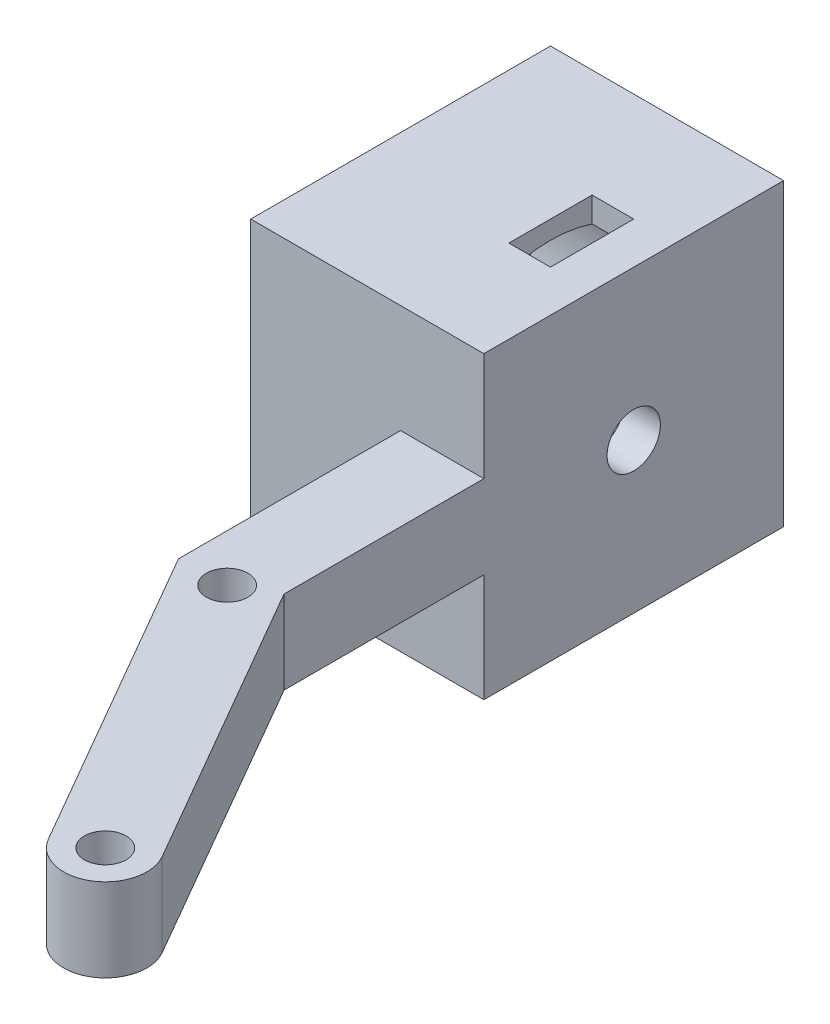
SolidWorks part; units mm, degrees
material "TPU 74D"
ref_plane "Front Plane" through (0, 0, 0) normal (0, 0, 1) x (1, 0, 0)
ref_plane "Top Plane" through (0, 0, 0) normal (0, 1, 0) x (1, 0, 0)
ref_plane "Right Plane" through (0, 0, 0) normal (1, 0, 0) x (0, 0, -1)
sketch "Sketch1" plane through (0, 0, 0) normal (0, 1, 0) x (1, 0, 0)
  line L0 (-6.35, -14.4015) -> (-6.35, 2.54)
  line L1 (0, -12.7) -> (0, 25.4)
  line L2 (0, 25.4) -> (-17.78, 25.4)
  line L3 (-17.78, 25.4) -> (-17.78, 2.54)
  line L4 (-17.78, 2.54) -> (-6.35, 2.54)
  line L5 (0, -12.7) -> (12.7, -34.697)
  line L6 (-6.35, -14.4015) -> (7.2007, -37.872)
  line L7 (0, -12.7) -> (-5.4993, -15.875) construction
  arc A0 (7.2007, -37.872) -> (12.7, -34.697) centre (9.9504, -36.2845) ccw
  circle A1 centre (9.9504, -36.2845) radius 1.5875
  circle A2 centre (-2.7496, -14.2875) radius 1.5875
  dimension "D1" = 3.175
  dimension "D2" = 3.175
  dimension "D6" = 3.175
  dimension "D3" = 150
  dimension "D4" = 6.35
  dimension "D8" = 25.4
  dimension "D10" = 17.78
  dimension "D11" = 38.1
  dimension "D12" = 22.86
  dimension "D13" = 12.7
extrude "Boss-Extrude1" add sketch "Sketch1" along normal blind 22.86
sketch "Sketch2" plane through (0, 22.86, 0) normal (0, 1, 0) x (1, 0, 0)
  line L1 (-6.35, -14.4015) -> (8.7882, -40.6217)
  line L2 (0, -12.7) -> (14.2875, -37.4467)
  line L3 (14.2875, -37.4467) -> (8.7882, -40.6217)
  line L4 (-6.35, -14.4015) -> (7.2007, -37.872) construction
  line L5 (12.7, -34.697) -> (0, -12.7) construction
  line L6 (-6.35, 2.54) -> (0, 2.54)
  line L7 (0, -12.7) -> (0, 25.4) construction
  line L8 (0, 2.54) -> (0, -12.7)
  line L9 (-6.35, -14.4015) -> (-6.35, 2.54)
  arc A0 (7.2007, -37.872) -> (12.7, -34.697) centre (9.9504, -36.2845) ccw construction
extrude "Top Cut" cut sketch "Sketch2" against normal blind 8.255
sketch "Sketch4" plane through (0, 0, 0) normal (0, -1, 0) x (1, 0, 0)
  line L0 (-6.35, -2.54) -> (-6.35, 14.4015)
  line L1 (-6.35, 14.4015) -> (7.2007, 37.872) construction
  line L2 (-6.35, -2.54) -> (-6.35, 14.4015) construction
  line L3 (-6.35, 14.4015) -> (8.7882, 40.6217)
  line L4 (8.7882, 40.6217) -> (14.2875, 37.4467)
  line L5 (-6.35, -2.54) -> (0, -2.54)
  line L7 (0, -2.54) -> (0, 12.7)
  line L8 (0, 12.7) -> (14.2875, 37.4467)
  line L9 (12.7, 34.697) -> (0, 12.7) construction
  arc A0 (12.7, 34.697) -> (7.2007, 37.872) centre (9.9504, 36.2845) ccw construction
extrude "Bottom Cut" cut sketch "Sketch4" against normal blind 8.255
sketch "Sketch3" plane through (0, 22.86, 0) normal (0, 1, 0) x (1, 0, 0)
  line L0 (-17.78, 25.4) -> (-19.05, 24.13)
  line L1 (-19.05, 24.13) -> (-17.78, 22.86)
  line L2 (-17.78, 25.4) -> (-17.78, 2.54) construction
  line L12 (-17.78, 25.4) -> (0, 25.4)
  line L13 (0, 25.4) -> (0, 0)
  line L14 (0, 2.54) -> (0, 25.4) construction
  line L16 (-19.05, 21.59) -> (-17.78, 20.32)
  line L17 (-17.78, 22.86) -> (-19.05, 21.59)
  line L18 (-19.05, 19.05) -> (-17.78, 17.78)
  line L19 (-17.78, 20.32) -> (-19.05, 19.05)
  line L20 (-19.05, 16.51) -> (-17.78, 15.24)
  line L21 (-17.78, 17.78) -> (-19.05, 16.51)
  line L22 (-19.05, 13.97) -> (-17.78, 12.7)
  line L23 (-17.78, 15.24) -> (-19.05, 13.97)
  line L24 (-19.05, 11.43) -> (-17.78, 10.16)
  line L25 (-17.78, 12.7) -> (-19.05, 11.43)
  line L26 (-19.05, 8.89) -> (-17.78, 7.62)
  line L27 (-17.78, 10.16) -> (-19.05, 8.89)
  line L28 (-19.05, 6.35) -> (-17.78, 5.08)
  line L29 (-17.78, 7.62) -> (-19.05, 6.35)
  line L30 (-19.05, 3.81) -> (-17.78, 2.54)
  line L31 (-17.78, 5.08) -> (-19.05, 3.81)
  line L32 (-19.05, 1.27) -> (-17.78, 0)
  line L33 (-17.78, 2.54) -> (-19.05, 1.27)
  line L34 (-17.78, 0) -> (0, 0)
  dimension "D1" = 2.54
  dimension "D2" = 135
  dimension "D3" = 10
extrude "Boss-Extrude2" [suppressed] add sketch "Sketch3" against normal up to surface (5.08 mm away) contours L13 L34 L32 L33 L30 L31 L28 L29 L26 L27 L24 L25 L22 L23 L20 L21 L18 L19 L16 L17 L1 L0 L12
sketch "Sketch5" plane through (-17.78, 0, 0) normal (-1, 0, 0) x (0, 0, 1)
  line L1 (-25.4, 0) -> (-2.54, 0)
  line L2 (-25.4, 0) -> (-25.4, 22.86)
  line L3 (-25.4, 22.86) -> (-2.54, 22.86)
  line L4 (-2.54, 0) -> (-2.54, 22.86)
  line L5 (-25.4, 0) -> (-2.54, 22.86) construction
  line L6 (-25.4, 22.86) -> (-2.54, 0) construction
  circle A0 centre (-13.97, 11.43) radius 10.033
  point P0 (-13.97, 11.43)
  dimension "D1" = 20.066
extrude "Cut-Extrude1" cut sketch "Sketch5" against normal blind 14.986 contours A0
sketch "Sketch7" plane through (0, 0, 0) normal (1, 0, 0) x (0, 0, -1)
  line L0 (2.54, 22.86) -> (25.4, 22.86) construction
  line L1 (2.54, 0) -> (25.4, 0)
  line L2 (2.54, 0) -> (2.54, 22.86)
  line L3 (2.54, 22.86) -> (25.4, 22.86)
  line L4 (25.4, 0) -> (25.4, 22.86)
  line L5 (2.54, 0) -> (25.4, 22.86) construction
  line L6 (2.54, 22.86) -> (25.4, 0) construction
  line L7 (25.4, 22.86) -> (25.4, 0) construction
  line L9 (2.54, 0) -> (25.4, 0) construction
  circle A0 centre (13.97, 11.43) radius 2.032
  point P0 (13.97, 11.43)
  dimension "D1" = 4.064
extrude "Cut-Extrude2" cut sketch "Sketch7" against normal through all contours A0
sketch "Sketch8" plane through (0, 22.86, 0) normal (0, 1, 0) x (1, 0, 0)
  line L0 (0, 2.54) -> (0, 25.4) construction
  line L1 (-6.35, 10.795) -> (-3.175, 10.795)
  line L2 (-6.35, 10.795) -> (-6.35, 17.145)
  line L3 (-6.35, 17.145) -> (-3.175, 17.145)
  line L4 (-3.175, 10.795) -> (-3.175, 17.145)
  line L5 (-6.35, 10.795) -> (-3.175, 17.145) construction
  line L6 (-6.35, 17.145) -> (-3.175, 10.795) construction
  line L7 (-17.78, 25.4) -> (-17.78, 2.54) construction
  line L11 (-17.78, 24.003) -> (-17.78, 3.937) construction
  point P0 (-4.7625, 13.97)
  point P12 (-17.78, 13.97)
  dimension "D1" = 3.175
  dimension "D2" = 6.35
  dimension "D3" = 3.175
extrude "Cut-Extrude3" cut sketch "Sketch8" against normal up to surface (1.9126 mm away)
sketch "Sketch9" [suppressed] plane through (0, 0, 0) normal (0, -1, 0) x (1, 0, 0)
  line L0 (0, -2.54) -> (0, -25.4) construction
  line L1 (-6.35, -17.145) -> (-3.175, -17.145)
  line L2 (-6.35, -17.145) -> (-6.35, -10.795)
  line L3 (-6.35, -10.795) -> (-3.175, -10.795)
  line L4 (-3.175, -17.145) -> (-3.175, -10.795)
  line L5 (-6.35, -17.145) -> (-3.175, -10.795) construction
  line L6 (-6.35, -10.795) -> (-3.175, -17.145) construction
  line L7 (-17.78, -2.54) -> (-17.78, -25.4) construction
  point P0 (-4.7625, -13.97)
  point P11 (-17.78, -13.97)
  dimension "D1" = 3.175
  dimension "D2" = 6.35
  dimension "D3" = 3.175
extrude "Cut-Extrude4" [suppressed] cut sketch "Sketch9" against normal up to next
